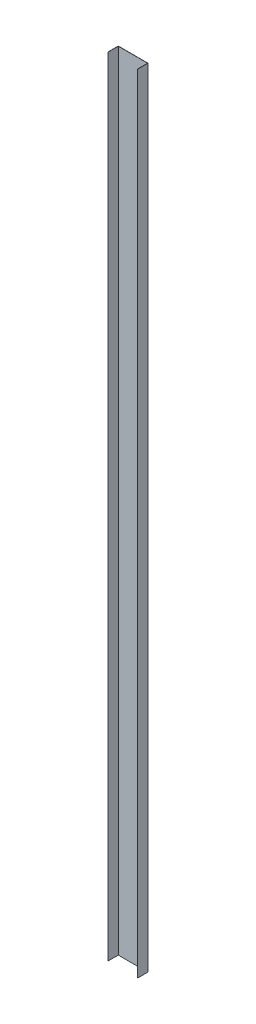
SolidWorks part; units mm, degrees
ref_plane "Front Plane" through (0, 0, 0) normal (0, 0, 1) x (1, 0, 0)
ref_plane "Top Plane" through (0, 0, 0) normal (0, 1, 0) x (1, 0, 0)
ref_plane "Right Plane" through (0, 0, 0) normal (1, 0, 0) x (0, 0, -1)
sketch "Sketch1" plane through (0, 0, 0) normal (0, 1, 0) x (1, 0, 0)
  line L0 (0, 0) -> (0, 31.219)
  line L1 (0, 31.219) -> (91.013, 31.219)
  line L2 (91.013, 31.219) -> (91.013, 0)
  line L3 (91.013, 0) -> (91.544, 0)
  line L4 (91.544, 0) -> (91.544, 31.75)
  line L5 (91.544, 31.75) -> (-0.531, 31.75)
  line L6 (-0.531, 31.75) -> (-0.531, 0)
  line L7 (-0.531, 0) -> (0, 0)
  line L8 (45.5065, 31.75) -> (45.5065, 31.219) construction
  dimension "D1" = 0.531
  dimension "D2" = 92.075
  dimension "D3" = 31.75
extrude "Boss-Extrude1" add sketch "Sketch1" along normal blind 2438.4
